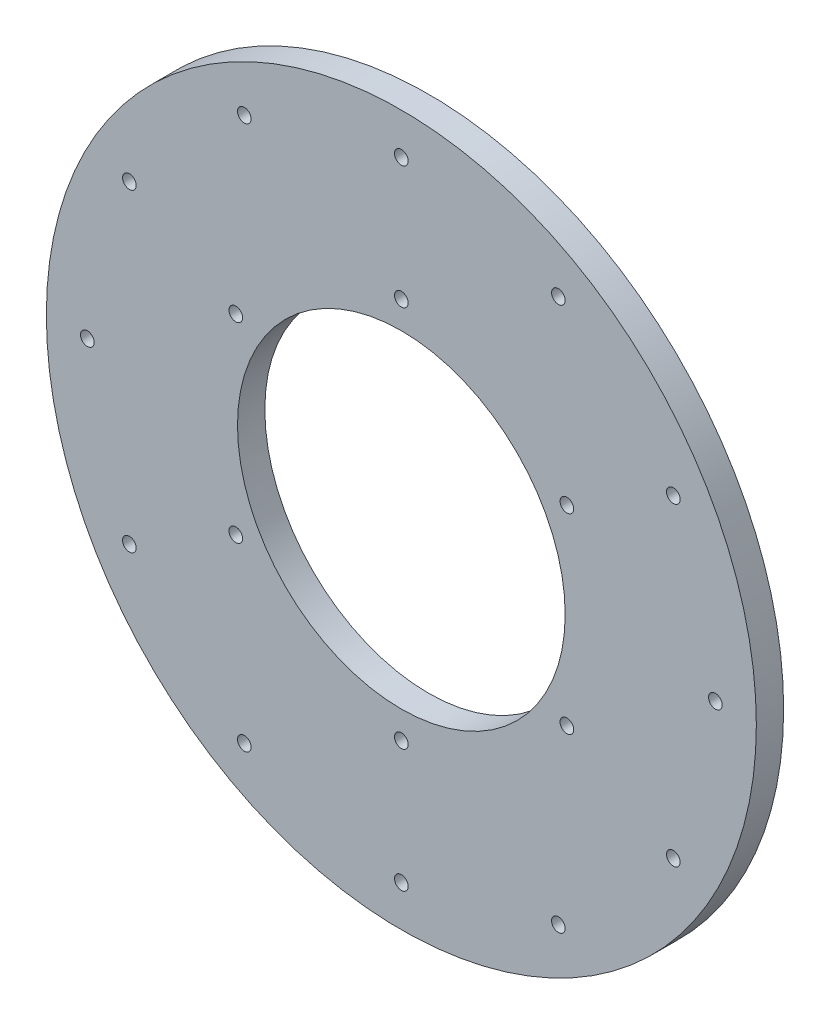
SolidWorks part; units mm, degrees
material "Thornel Mat VMA"
ref_plane "前视基准面" through (0, 0, 0) normal (0, 0, 1) x (1, 0, 0)
ref_plane "上视基准面" through (0, 0, 0) normal (0, 1, 0) x (1, 0, 0)
ref_plane "右视基准面" through (0, 0, 0) normal (1, 0, 0) x (0, 0, -1)
other "Configuration Table"
sketch "草图1" plane through (0, 0, 0) normal (0, 0, 1) x (1, 0, 0)
  circle A0 centre (0, 0) radius 60
  circle A1 centre (0, 0) radius 130
  dimension "D1" = 120
  dimension "D2" = 260
extrude "凸台-拉伸1" add sketch "草图1" along normal blind 10
sketch "草图2" plane through (0, 0, 10) normal (0, 0, 1) x (1, 0, 0)
  circle A0 centre (0, 0) radius 70 construction
  circle A1 centre (0, 70) radius 2.5
  circle A2 centre (60.6218, 35) radius 2.5
  circle A3 centre (60.6218, -35) radius 2.5
  circle A4 centre (0, -70) radius 2.5
  circle A5 centre (-60.6218, -35) radius 2.5
  circle A6 centre (-60.6218, 35) radius 2.5
  point P17 (0, 0)
  dimension "D1" = 140
  dimension "D2" = 5
  dimension "D3" = 6
extrude "切除-拉伸1" cut sketch "草图2" against normal through all
sketch "草图3" plane through (0, 0, 10) normal (0, 0, 1) x (1, 0, 0)
  circle A0 centre (0, 0) radius 115 construction
  circle A1 centre (0, 115) radius 2.5
  circle A2 centre (57.5, 99.5929) radius 2.5
  circle A3 centre (99.5929, 57.5) radius 2.5
  circle A4 centre (115, 0) radius 2.5
  circle A5 centre (99.5929, -57.5) radius 2.5
  circle A6 centre (57.5, -99.5929) radius 2.5
  circle A7 centre (0, -115) radius 2.5
  circle A8 centre (-57.5, -99.5929) radius 2.5
  circle A9 centre (-99.5929, -57.5) radius 2.5
  circle A10 centre (-115, 0) radius 2.5
  circle A11 centre (-99.5929, 57.5) radius 2.5
  circle A12 centre (-57.5, 99.5929) radius 2.5
  point P29 (0, 0)
  dimension "D1" = 230
  dimension "D2" = 5
  dimension "D3" = 12
extrude "切除-拉伸2" cut sketch "草图3" against normal through all
